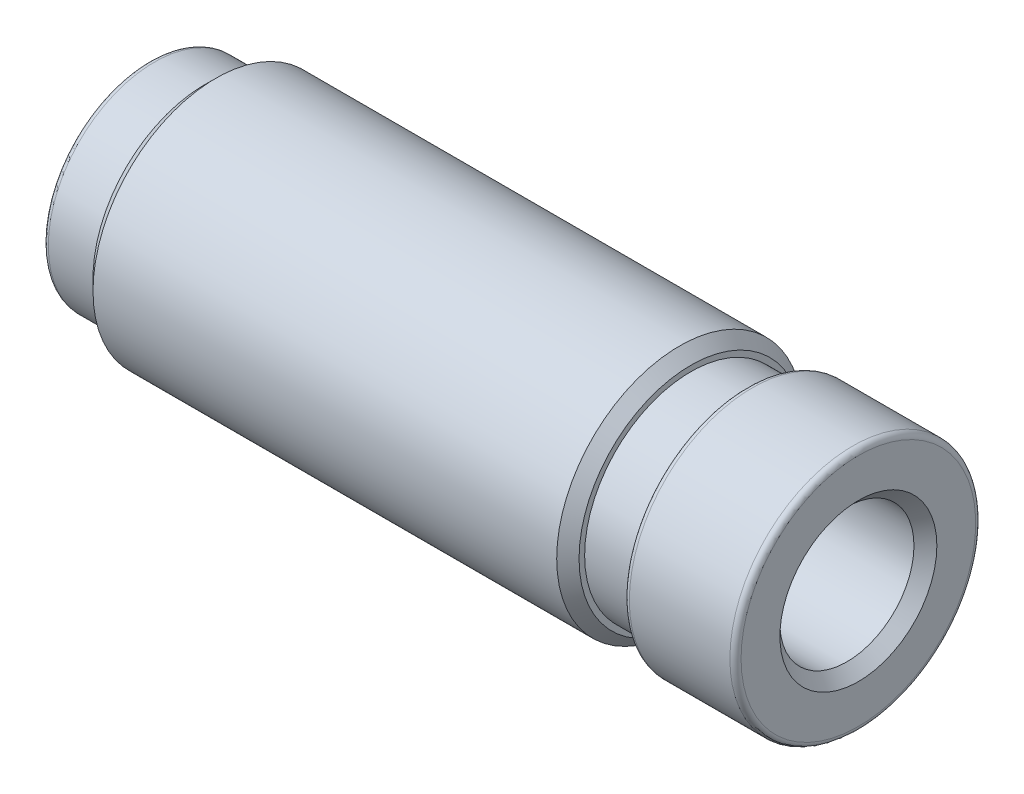
SolidWorks part; units mm, degrees
ref_plane "Plano frontal" through (0, 0, 0) normal (0, 0, 1) x (1, 0, 0)
ref_plane "Plano superior" through (0, 0, 0) normal (0, 1, 0) x (1, 0, 0)
ref_plane "Plano direito" through (0, 0, 0) normal (1, 0, 0) x (0, 0, -1)
sketch "Esboço1" plane through (0, 0, 0) normal (0, 0, 1) x (1, 0, 0)
  line L0 (0, 0) -> (63.5, 0)
  line L1 (63.5, 0) -> (63.5, 11)
  line L2 (63.5, 11) -> (53.5, 11)
  line L3 (53.5, 11) -> (53.5, 9.5)
  line L4 (53.5, 9.5) -> (48.5, 9.5)
  line L5 (48.5, 9.5) -> (48.5, 11)
  line L6 (48.5, 11) -> (5, 11)
  line L7 (5, 11) -> (5, 9.5)
  line L8 (5, 9.5) -> (0, 9.5)
  line L9 (0, 9.5) -> (0, 0)
  point P8 (2.5, 9.5)
  point P11 (51, 9.5)
  point P12 (26.75, 11)
  point P13 (58.5, 11)
  dimension "D1" = 11
  dimension "D2" = 10
  dimension "D3" = 5
  dimension "D4" = 1.5
  dimension "D5" = 63.5
  dimension "D6" = 5
revolve "Revolução1" add sketch "Esboço1" angle 360 about L0
cosmetic thread "Representação de rosca1" parameters "D2"=20.344
hole_wizard "Furo roscado de M14x2.01" positions "Esboço2" profile "Esboço3" tap size "M14x2.0" standard "Ansi Metric"
sketch "Esboço2" plane through (63.5, 0, 0) normal (1, 0, 0) x (0, 0, -1)
  point P0 (0, 0)
sketch "Esboço3" plane through (63.5, 0, 0) normal (0, 1, 0) x (0, 0, -1)
  line L0 (0, 0) -> (0, 57.1052)
  line L1 (0, 57.1052) -> (6, 53.5)
  line L2 (6, 53.5) -> (6, 1.025)
  line L3 (6, 1.025) -> (7.025, 0)
  line L5 (7.025, 0) -> (0, 0)
  line L6 (-6, 1.025) -> (-7.025, 0) construction
  line L10 (0, 57.1052) -> (-6, 53.5) construction
  line L11 (0, -6.35) -> (0, 107.95) construction
  dimension "Tap Drill Dia." = 12
  dimension "Tap Drill Depth" = 53.5
  dimension "Near C'Sink Dia." = 14.05
  dimension "Near C'Sink Angle" = 90
  dimension "Drill Angle" = 118
cosmetic thread "Rosca de furo1" parameters "D1"=38, "D2"=14
hole_wizard "Furo1" positions "Esboço6" profile "Esboço7" legacy
sketch "Esboço6" plane through (0, 0, 0) normal (-1, 0, 0) x (0, 0, 1)
  point P0 (0, 0)
sketch "Esboço7" plane through (0, 0, 0) normal (0, 1, 0) x (0, 0, 1)
  line L0 (0, 0) -> (0, 10)
  line L1 (0, 10) -> (4.7, 10)
  line L2 (4.7, 10) -> (4.7, 0)
  line L3 (4.7, 0) -> (0, 0)
  line L4 (0, 110) -> (0, -10) construction
  dimension "Diameter" = 9.4
  dimension "Depth" = 10
chamfer "Chanfro1" distance 1 angle 45 2 edges at (48.5, 0, 11) (5, 0, 11)
fillet "Filete1" radius 0.5 4 edges at (0, 0, 4.7) (0, 0, 9.5) (53.5, 0, 11) (63.5, 0, 11)
